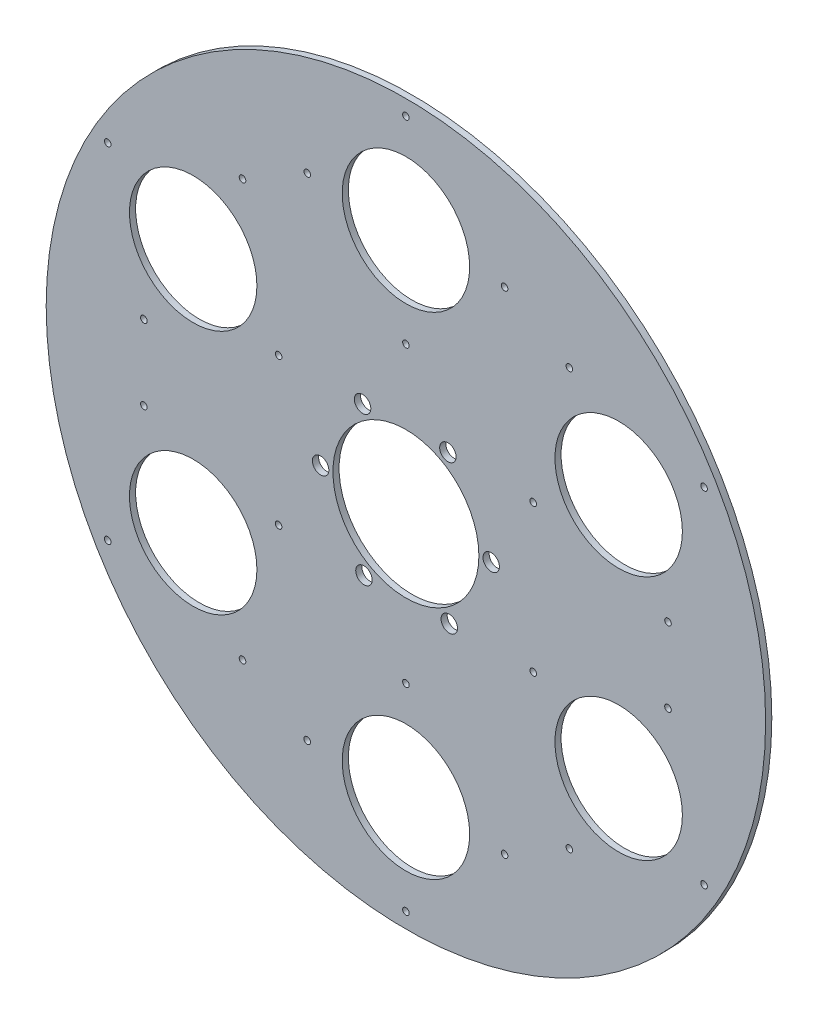
SolidWorks part; units mm, degrees
ref_plane "Front Plane" through (0, 0, 0) normal (0, 0, 1) x (1, 0, 0)
ref_plane "Top Plane" through (0, 0, 0) normal (0, 1, 0) x (1, 0, 0)
ref_plane "Right Plane" through (0, 0, 0) normal (1, 0, 0) x (0, 0, -1)
sketch "Sketch1" plane through (0, 0, 0) normal (0, 0, 1) x (1, 0, 0)
  circle A0 centre (0, 0) radius 175
  circle A1 centre (0, 0) radius 35.5
  circle A5 centre (0, 119.5) radius 31
  circle A6 centre (103.49, 59.75) radius 31
  circle A7 centre (103.49, -59.75) radius 31
  circle A8 centre (0, -119.5) radius 31
  circle A9 centre (-103.49, -59.75) radius 31
  circle A10 centre (-103.49, 59.75) radius 31
  point P20 (0, 0)
  dimension "D1" = 6
extrude "Boss-Extrude1" add sketch "Sketch1" against normal blind 3
sketch "Sketch2" plane through (0, 0, 0) normal (0, 0, 1) x (1, 0, 0)
  circle A1 centre (0, 71.5) radius 1.6
  circle A2 centre (-48, 119.5) radius 1.6
  circle A3 centre (0, 167.5) radius 1.6
  circle A4 centre (48, 119.5) radius 1.6
  circle A6 centre (61.9208, 35.75) radius 1.6
  circle A7 centre (79.49, 101.3192) radius 1.6
  circle A9 centre (145.0593, 83.75) radius 1.6
  circle A11 centre (127.49, 18.1808) radius 1.6
  circle A13 centre (61.9208, -35.75) radius 1.6
  circle A15 centre (127.49, -18.1808) radius 1.6
  circle A17 centre (145.0593, -83.75) radius 1.6
  circle A19 centre (79.49, -101.3192) radius 1.6
  circle A21 centre (0, -71.5) radius 1.6
  circle A22 centre (48, -119.5) radius 1.6
  circle A23 centre (0, -167.5) radius 1.6
  circle A24 centre (-48, -119.5) radius 1.6
  circle A25 centre (-61.9208, -35.75) radius 1.6
  circle A26 centre (-79.49, -101.3192) radius 1.6
  circle A27 centre (-145.0593, -83.75) radius 1.6
  circle A28 centre (-127.49, -18.1808) radius 1.6
  circle A29 centre (-61.9208, 35.75) radius 1.6
  circle A30 centre (-127.49, 18.1808) radius 1.6
  circle A31 centre (-145.0593, 83.75) radius 1.6
  circle A32 centre (-79.49, 101.3192) radius 1.6
  point P50 (0, 0)
  dimension "D1" = 6
extrude "Cut-Extrude1" cut sketch "Sketch2" against normal blind 3
sketch "Sketch3" plane through (0, 0, 0) normal (0, 0, 1) x (1, 0, 0)
  line L0 (-30.3, -17.4937) -> (0, -34.9874)
  line L1 (-30.3, 17.4937) -> (-30.3, -17.4937)
  line L2 (0, 34.9874) -> (-30.3, 17.4937)
  line L3 (30.3, 17.4937) -> (0, 34.9874)
  line L4 (30.3, -17.4937) -> (30.3, 17.4937)
  line L5 (0, -34.9874) -> (30.3, -17.4937)
  circle A0 centre (-41.4982, -0.3841) radius 4
  circle A1 centre (41.4982, 0.3841) radius 4
  circle A2 centre (20.4164, 36.1306) radius 4
  circle A3 centre (-21.0818, 35.7464) radius 4
  circle A4 centre (21.0818, -35.7464) radius 4
  circle A5 centre (-20.4164, -36.1306) radius 4
  circle A6 centre (0, 0) radius 50
  circle A8 centre (0, 0) radius 35.5
  point P20 (0, 0)
extrude "Cut-Extrude2" cut sketch "Sketch3" against normal blind 3 contours A3 | A2 | A1 | A0 | A5 | A4
